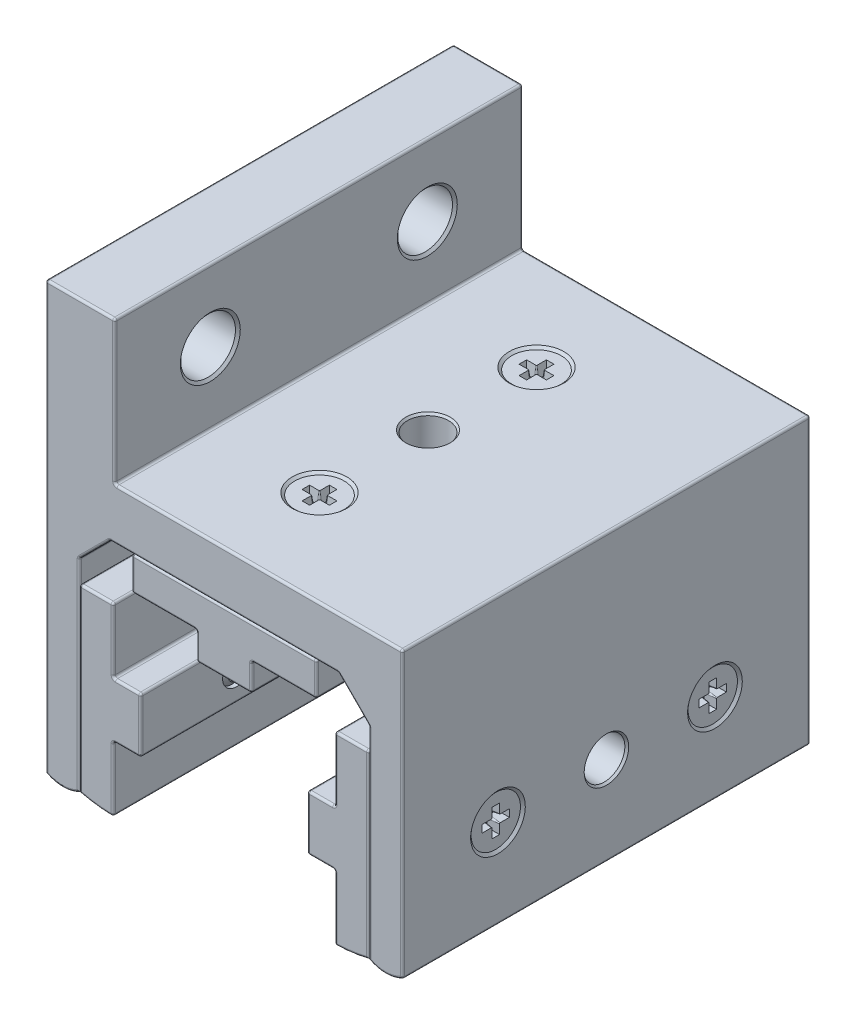
SolidWorks part; units mm, degrees
ref_plane "Front Plane" through (0, 0, 0) normal (0, 0, 1) x (1, 0, 0)
ref_plane "Top Plane" through (0, 0, 0) normal (0, 1, 0) x (1, 0, 0)
ref_plane "Right Plane" through (0, 0, 0) normal (1, 0, 0) x (0, 0, -1)
sketch "Sketch1" plane through (0, 0, 0) normal (0, 0, 1) x (1, 0, 0)
  line L0 (-20.56, -24.865) -> (-20.56, 24.865)
  line L1 (-20.56, 24.865) -> (-12.58, 24.865)
  line L2 (-12.58, 24.865) -> (-12.58, 8.385)
  line L3 (-12.58, 8.385) -> (20.56, 8.385)
  line L4 (20.56, 8.385) -> (20.56, -24.865)
  line L5 (20.56, -24.865) -> (16.66, -24.865)
  line L6 (16.66, -24.865) -> (16.66, -3.565)
  line L8 (10.65, 2.485) -> (-10.65, 2.485)
  line L10 (-16.66, -3.565) -> (-16.66, -24.865)
  line L11 (-16.66, -24.865) -> (-20.56, -24.865)
  line L12 (-16.66, -24.865) -> (-12.76, -24.865)
  line L13 (-12.76, -24.865) -> (-12.76, -17.39)
  line L14 (-12.76, -17.39) -> (-9.585, -17.39)
  line L15 (-9.585, -17.39) -> (-9.585, -11.04)
  line L16 (-9.585, -11.04) -> (-12.76, -11.04)
  line L17 (-12.76, -11.04) -> (-12.76, -3.565)
  line L18 (-12.76, -3.565) -> (-16.66, -3.565)
  line L19 (0, 0) -> (0, 8.385) construction
  line L20 (-16.66, -3.565) -> (-16.66, -1.0356)
  line L21 (-10.65, -1.415) -> (-3.175, -1.415)
  line L22 (-3.175, -1.415) -> (-3.175, -4.59)
  line L23 (-3.175, -4.59) -> (3.175, -4.59)
  line L24 (10.65, -1.415) -> (3.175, -1.415)
  line L25 (-16.66, -1.0356) -> (-13.1394, 2.485)
  line L26 (3.175, -4.59) -> (3.175, -1.415)
  line L27 (-13.1394, 2.485) -> (-10.65, 2.485)
  line L28 (-10.65, -1.415) -> (-10.65, 2.485)
  line L29 (10.65, -1.415) -> (10.65, 2.485)
  line L30 (-20.56, 8.385) -> (0, 8.385) construction
  line L31 (0, 8.385) -> (20.56, 8.385) construction
  line L32 (-14.8997, 0.7247) -> (-13.1394, 2.485) construction
  line L33 (13.1394, 2.485) -> (10.65, 2.485)
  line L34 (16.66, -3.565) -> (16.66, -1.0356)
  line L35 (16.66, -1.0356) -> (13.1394, 2.485)
  point P0 (0, 0)
  point P3 (-20.56, 0)
  point P16 (-9.585, -14.215)
  point P30 (0, -4.59)
  dimension "Length (B)" = 49.73
  dimension "Length (A)" = 41.12
  dimension "Length (C)" = 33.25
  dimension "D2" = 3.9
  dimension "Top to Centerline" = 39.08
  dimension "D3" = 6.35
  dimension "Inside Width" = 7.8
  dimension "Mounting Hole Depth" = 7.98
  dimension "D" = 9.8
  dimension "D4" = 6.35
  dimension "D5" = 3.175
  dimension "D1" = 45
sketch "Sketch2" plane through (0, 0, 0) normal (-1, 0, 0) x (0, 1, 0)
  line L0 (0, -23.5) -> (0, 23.5) construction
  line L3 (8.405, 0) -> (24.865, 0) construction
  line L4 (16.635, -23.5) -> (16.635, 23.5) construction
  circle A0 centre (16.635, -12.5) radius 3.15
  circle A1 centre (-14.215, -12.5) radius 3.15
  point P4 (0, 0)
  point P10 (16.635, 0)
  point P12 (16.635, 12.5)
  point P15 (24.865, 0)
  point P21 (-14.215, 0)
  dimension "Mounting Hole Diameter" = 6.3
  dimension "Length" = 47
  dimension "Hole to Edge" = 11
  dimension "Hole Spacing" = 25
  dimension "Hole to Top" = 8.23
sketch "Sketch3" plane through (0, 0, 0) normal (0, 0, 1) x (1, 0, 0)
  line L0 (-20.56, -24.865) -> (-20.56, 24.865)
  line L1 (-20.56, 24.865) -> (-12.58, 24.865)
  line L2 (-12.58, 24.865) -> (-12.58, 8.385)
  line L3 (-12.58, 8.385) -> (20.56, 8.385)
  line L4 (20.56, 8.385) -> (20.56, -24.865)
  line L5 (20.56, -24.865) -> (16.66, -24.865)
  line L6 (16.66, -24.865) -> (16.66, -1.0356)
  line L7 (16.66, -1.0356) -> (13.1394, 2.485)
  line L8 (13.1394, 2.485) -> (-13.1394, 2.485)
  line L9 (-13.1394, 2.485) -> (-16.66, -1.0356)
  line L10 (-16.66, -1.0356) -> (-16.66, -24.865)
  line L11 (-16.66, -24.865) -> (-20.56, -24.865)
extrude "Boss-Extrude1" add sketch "Sketch3" along normal up to vertex (23.5 mm away) and the other way up to vertex (23.5 mm away) up to point (0, 16.635, 23.5) other way up to point (0, 16.635, -23.5)
sketch "Sketch4" plane through (0, 0, 0) normal (0, 0, 1) x (1, 0, 0)
  line L0 (-16.66, -3.565) -> (-12.76, -3.565)
  line L1 (-12.76, -3.565) -> (-12.76, -11.04)
  line L2 (-12.76, -11.04) -> (-9.585, -11.04)
  line L3 (-9.585, -11.04) -> (-9.585, -17.39)
  line L4 (-9.585, -17.39) -> (-12.76, -17.39)
  line L5 (-12.76, -17.39) -> (-12.76, -24.865)
  line L6 (-12.76, -24.865) -> (-16.66, -24.865)
  line L7 (-16.66, -24.865) -> (-16.66, -3.565)
  line L8 (-10.65, 2.485) -> (-10.65, -1.415)
  line L9 (-10.65, -1.415) -> (-3.175, -1.415)
  line L10 (-3.175, -1.415) -> (-3.175, -4.59)
  line L11 (-3.175, -4.59) -> (3.175, -4.59)
  line L12 (3.175, -4.59) -> (3.175, -1.415)
  line L13 (3.175, -1.415) -> (10.65, -1.415)
  line L14 (10.65, -1.415) -> (10.65, 2.485)
  line L15 (10.65, 2.485) -> (-10.65, 2.485)
  line L16 (0, -11.065) -> (0, -17.365) construction
  line L17 (0, -11.065) -> (0, -17.365) construction
  line L18 (16.66, -24.865) -> (16.66, -3.565)
  line L19 (12.76, -24.865) -> (16.66, -24.865)
  line L20 (12.76, -17.39) -> (12.76, -24.865)
  line L21 (9.585, -17.39) -> (12.76, -17.39)
  line L22 (9.585, -11.04) -> (9.585, -17.39)
  line L23 (12.76, -11.04) -> (9.585, -11.04)
  line L24 (12.76, -3.565) -> (12.76, -11.04)
  line L25 (16.66, -3.565) -> (12.76, -3.565)
extrude "Boss-Extrude2" add sketch "Sketch4" along normal up to vertex (23.5 mm away) and the other way up to vertex (23.5 mm away) separate body up to point (0, 0, 23.5) other way up to point (0, 0, -23.5)
sketch "Sketch5" plane through (0, 0, 0) normal (1, 0, 0) x (0, 0, -1)
  circle A0 centre (-12.5, -14.215) radius 3.15 construction
  circle A1 centre (-12.5, 16.635) radius 3.15 construction
  circle A2 centre (-12.5, -14.215) radius 3.15 construction
  circle A3 centre (-12.5, 16.635) radius 3.15
extrude "Cut-Extrude1" cut sketch "Sketch5" against normal through all both and the other way through all
sketch "Sketch6" plane through (0, 0, 0) normal (1, 0, 0) x (0, 0, -1)
  circle A0 centre (-12.5, -14.215) radius 1.575
  dimension "D1" = 3.15
extrude "Cut-Extrude2" cut sketch "Sketch6" against normal through all both and the other way through all
sketch "Sketch7" plane through (0, 8.385, 0) normal (0, 1, 0) x (1, 0, 0)
  line L1 (0, -9.35) -> (0, -15.65) construction
  line L2 (0, -23.5) -> (0, 23.5) construction
  line L3 (3.15, -12.5) -> (-3.15, -12.5) construction
  line L4 (0, -9.35) -> (0, -15.65) construction
  circle A0 centre (0, -12.5) radius 3.15
extrude "Cut-Extrude3" cut sketch "Sketch7" against normal through all draft 50
sketch "Sketch9" plane through (20.56, 0, 0) normal (1, 0, 0) x (0, 0, -1)
  circle A0 centre (-12.5, -14.215) radius 3.15 construction
  circle A1 centre (-12.5, -14.215) radius 3.15
extrude "Cut-Extrude4" cut sketch "Sketch9" against normal blind 2.54 draft 50
sketch "Sketch10" plane through (-20.56, 0, 0) normal (-1, 0, 0) x (0, 0, 1)
  circle A0 centre (12.5, -14.215) radius 3.15 construction
  circle A1 centre (12.5, -14.215) radius 3.15
extrude "Cut-Extrude5" cut sketch "Sketch10" against normal blind 2.54 draft 50
chamfer "Chamfer2" distance 0.254 angle 50 1 edges at (-12.58, 13.485, 12.5)
sketch "Sketch11" plane through (0, 8.385, 0) normal (0, 1, 0) x (1, 0, 0)
  line L0 (0, -9.35) -> (0, -15.65) construction
  circle A0 centre (0, -12.5) radius 1.575
  dimension "D1" = 3.15
extrude "Cut-Extrude6" cut sketch "Sketch11" against normal through all
sketch "Sketch12" plane through (0, 0, 0) normal (1, 0, 0) x (0, 0, -1)
  line L0 (-12.5, -12.64) -> (-12.5, -11.065) construction
  line L1 (-12.5, -11.8525) -> (0, -11.8525) construction
  circle A0 centre (0, -14.215) radius 2.3625
  circle A1 centre (-12.5, -14.215) radius 1.575 construction
  circle A2 centre (-12.5, -14.215) radius 3.15 construction
extrude "Cut-Extrude7" cut sketch "Sketch12" against normal through all both and the other way through all
sketch "Sketch13" plane through (0, 8.385, 0) normal (0, 1, 0) x (1, 0, 0)
  line L0 (0, -23.5) -> (0, 23.5) construction
  line L1 (-1.575, -12.5) -> (-3.15, -12.5) construction
  line L2 (-2.3625, -12.5) -> (-2.3625, 0) construction
  circle A0 centre (0, 0) radius 2.3625
  circle A1 centre (0, -12.5) radius 1.575 construction
  circle A2 centre (0, -12.5) radius 3.15 construction
extrude "Cut-Extrude8" cut sketch "Sketch13" against normal through all
sketch "Sketch14" plane through (0, 0, 0) normal (0, 0, 1) x (1, 0, 0)
  line L0 (-20.56, -24.865) -> (-20.56, 24.865) construction
  line L1 (-16.66, -3.565) -> (-16.66, -24.865) construction
  line L2 (-16.66, -24.865) -> (-20.56, -24.865) construction
  line L3 (-20.56, -24.357) -> (-20.56, -24.865)
  line L4 (-20.56, -24.865) -> (-20.56, -25.373)
  line L5 (-20.56, -25.373) -> (-16.66, -25.373)
  line L6 (-16.66, -25.373) -> (-16.66, -24.357) construction
  line L7 (-16.66, -24.865) -> (-12.76, -24.865) construction
  line L8 (-16.66, -25.373) -> (-12.76, -25.373)
  line L9 (-12.76, -25.373) -> (-12.76, -24.865)
  line L10 (0, -11.065) -> (0, -17.365) construction
  line L11 (0, -11.065) -> (0, -17.365) construction
  line L12 (16.66, -25.373) -> (16.66, -24.357) construction
  line L13 (12.76, -25.373) -> (12.76, -24.865)
  line L14 (16.66, -25.373) -> (12.76, -25.373)
  line L15 (20.56, -25.373) -> (16.66, -25.373)
  line L16 (20.56, -24.865) -> (20.56, -25.373)
  line L17 (20.56, -24.357) -> (20.56, -24.865)
  arc A0 (-20.56, -24.357) -> (-16.66, -24.357) centre (-18.61, -20.8684) ccw
  arc A1 (-12.76, -24.865) -> (-16.66, -24.357) centre (-12.76, -9.6405) cw
  arc A2 (12.76, -24.865) -> (16.66, -24.357) centre (12.76, -9.6405) ccw
  arc A3 (20.56, -24.357) -> (16.66, -24.357) centre (18.61, -20.8684) cw
  dimension "D1" = 0.508
extrude "Cut-Extrude9" cut sketch "Sketch14" against normal through all both and the other way through all
fillet "Fillet1" radius 0.254 34 edges at (-20.56, 24.865, 0) (-20.56, -24.357, 0) (-16.66, -12.6963, -23.5) (-14.8997, 0.7247, -23.5) (0, 2.485, -23.5) (14.8997, 0.7247, -23.5) (16.66, -12.6963, -23.5) (18.61, -24.865, -23.5) (20.56, -7.986, -23.5) (3.99, 8.385, -23.5) (-12.58, 16.625, -23.5) (-16.57, 24.865, -23.5) (-20.56, 0.254, -23.5) (-18.61, -24.865, -23.5) (-16.57, 24.865, 23.5) (-12.58, 16.625, 23.5) (3.99, 8.385, 23.5) (20.56, -7.986, 23.5) (18.61, -24.865, 23.5) (16.66, -12.6963, 23.5) (14.8997, 0.7247, 23.5) (0, 2.485, 23.5) (-14.8997, 0.7247, 23.5) (-16.66, -12.6963, 23.5) (-18.61, -24.865, 23.5) (-20.56, 0.254, 23.5) (-12.58, 24.865, 0) (20.56, -24.357, 0) (-12.58, 8.385, 0) (20.56, 8.385, 0) (-13.1394, 2.485, 0) (-16.66, -1.0356, 0) (16.66, -1.0356, 0) (13.1394, 2.485, 0)
fillet "Fillet2" radius 0.254 23 edges at (-12.76, -3.565, 0) (-12.76, -11.04, 0) (-12.76, -17.39, 0) (-12.76, -24.865, 0) (-12.76, -21.1275, -23.5) (-11.1725, -17.39, -23.5) (-9.585, -14.215, -23.5) (-11.1725, -11.04, -23.5) (-12.76, -7.3025, -23.5) (-14.71, -3.565, -23.5) (-16.66, -13.961, -23.5) (-14.7265, -24.7375, -23.5) (-14.71, -3.565, 23.5) (-12.76, -7.3025, 23.5) (-11.1725, -11.04, 23.5) (-9.585, -14.215, 23.5) (-11.1725, -17.39, 23.5) (-12.76, -21.1275, 23.5) (-14.7265, -24.7375, 23.5) (-16.66, -13.961, 23.5) (-9.585, -17.39, 0) (-9.585, -11.04, 0) (-16.66, -3.565, 0)
fillet "Fillet3" radius 0.254 23 edges at (12.76, -11.04, 0) (12.76, -3.565, 0) (14.71, -3.565, -23.5) (12.76, -7.3025, -23.5) (11.1725, -11.04, -23.5) (9.585, -14.215, -23.5) (11.1725, -17.39, -23.5) (14.7265, -24.7375, -23.5) (16.66, -13.961, -23.5) (11.1725, -17.39, 23.5) (9.585, -14.215, 23.5) (11.1725, -11.04, 23.5) (12.76, -7.3025, 23.5) (14.71, -3.565, 23.5) (16.66, -13.961, 23.5) (14.7265, -24.7375, 23.5) (12.76, -21.1275, 23.5) (12.76, -24.865, 0) (12.76, -21.1275, -23.5) (12.76, -17.39, 0) (9.585, -11.04, 0) (9.585, -17.39, 0) (16.66, -3.565, 0)
sketch "Sketch15" plane through (20.56, 0, 0) normal (1, 0, 0) x (0, 0, -1)
  circle A2 centre (-12.5, -14.215) radius 2.8452
  circle A3 centre (-12.5, -14.215) radius 2.8452
  dimension "D1" = 0.3048
extrude "Boss-Extrude3" add sketch "Sketch15" against normal blind 2.54 draft 50 from offset 0.254 separate body offset against normal yes
sketch "Sketch16" plane through (20.306, 0, 0) normal (1, 0, 0) x (0, 0, -1)
  circle A0 centre (-12.5, -14.215) radius 1.575 construction
  circle A1 centre (-12.5, -14.215) radius 1.575
extrude "Boss-Extrude4" add sketch "Sketch16" against normal up to surface (10.721 mm away) up to face at (9.585, -14.215, 0)
chamfer "Chamfer3" distance 0.508 angle 50 1 edges at (9.585, -14.215, 10.925)
sketch "Sketch17" plane through (20.306, 0, 0) normal (1, 0, 0) x (0, 0, -1)
  line L1 (-12.754, -15.612) -> (-12.246, -15.612)
  line L2 (-12.754, -15.612) -> (-12.754, -12.818)
  line L3 (-12.754, -12.818) -> (-12.246, -12.818)
  line L4 (-12.246, -15.612) -> (-12.246, -12.818)
  line L5 (-12.5, -12.818) -> (-12.5, -15.612) construction
  line L6 (-12.754, -14.215) -> (-12.246, -14.215) construction
  line L7 (-13.897, -14.469) -> (-11.103, -14.469)
  line L8 (-13.897, -14.469) -> (-13.897, -13.961)
  line L9 (-13.897, -13.961) -> (-11.103, -13.961)
  line L10 (-11.103, -14.469) -> (-11.103, -13.961)
  line L11 (-12.5, -13.961) -> (-12.5, -14.469) construction
  line L12 (-13.897, -14.215) -> (-11.103, -14.215) construction
  point P0 (-12.5, -14.215)
  point P4 (-12.5, -14.215)
  dimension "D1" = 0.508
  dimension "D2" = 0.508
  dimension "D3" = 2.794
extrude "Cut-Extrude10" cut sketch "Sketch17" against normal blind 1.27 contours L9 L8 L7 L2 | L9 L2 L7 L4 | L7 L10 L9 L4 | L2 L9 L4 L3 | L7 L2 L1 L4
fillet "Fillet4" radius 0.254 4 edges at (19.671, -14.469, 12.246) (19.671, -14.469, 12.754) (19.671, -13.961, 12.246) (19.671, -13.961, 12.754)
draft "Draft1" type of draft neutral plane draft angle 8 faces to draft 16 face at (19.671, -13.2625, 12.754) face at (19.671, -13.8603, 12.8547) face at (19.671, -13.961, 13.4525) face at (19.671, -13.961, 11.5475) face at (19.671, -13.8603, 12.1453) face at (19.671, -13.2625, 12.246) face at (19.671, -15.1675, 12.246) face at (19.671, -14.5697, 12.1453) face at (19.671, -14.469, 11.5475) face at (19.671, -14.469, 13.4525) face at (19.671, -14.5697, 12.8547) face at (19.671, -15.1675, 12.754) face at (19.671, -15.612, 12.5) face at (19.671, -14.215, 13.897) face at (19.671, -12.818, 12.5) face at (19.671, -14.215, 11.103) neutral plane through (19.036, 0, 0) neutral plane normal (1, 0, 0) parameters "D1"=8
sketch "Sketch18" plane through (0, 0, 0) normal (1, 0, 0) x (0, 0, -1)
  line L0 (-9.35, 8.385) -> (-15.65, 8.385) construction
  line L1 (-9.35, 8.385) -> (-15.65, 8.385) construction
  line L2 (-15.65, 8.385) -> (-12.5, 5.7418) construction
  line L3 (-12.5, 5.7418) -> (-9.35, 8.385) construction
  line L4 (-12.5, 5.7418) -> (-12.5, 8.131)
  line L5 (23.246, 8.131) -> (-23.246, 8.131) construction
  line L6 (-12.5, 8.131) -> (-15.3473, 8.131)
  line L7 (-15.3473, 8.131) -> (-14.075, 7.0634)
  line L8 (-14.075, 7.0634) -> (-14.075, -4.082)
  line L9 (-13.567, -4.59) -> (-12.5, -4.59)
  line L10 (-12.5, -4.59) -> (-12.5, 5.7418)
  line L11 (-14.075, -4.59) -> (-10.925, -4.59) construction
  line L12 (-14.075, -4.59) -> (-10.925, -4.59) construction
  line L13 (-14.075, -4.082) -> (-13.567, -4.59)
  point P9 (-14.075, -4.59)
  dimension "D1" = 100
revolve "Revolve1" add sketch "Sketch18" angle 360 about L10
sketch "Sketch19" plane through (0, 8.131, 0) normal (0, 1, 0) x (1, 0, 0)
  line L0 (0, -9.35) -> (0, -15.65) construction
  line L1 (-0.254, -13.897) -> (0.254, -13.897)
  line L2 (-0.254, -13.897) -> (-0.254, -11.103)
  line L3 (-0.254, -11.103) -> (0.254, -11.103)
  line L4 (0.254, -13.897) -> (0.254, -11.103)
  line L5 (0, -11.103) -> (0, -13.897) construction
  line L6 (-0.254, -12.5) -> (0.254, -12.5) construction
  line L8 (-1.397, -12.754) -> (1.397, -12.754)
  line L9 (-1.397, -12.754) -> (-1.397, -12.246)
  line L10 (-1.397, -12.246) -> (1.397, -12.246)
  line L11 (1.397, -12.754) -> (1.397, -12.246)
  line L12 (0, -12.246) -> (0, -12.754) construction
  line L13 (-1.397, -12.5) -> (1.397, -12.5) construction
  point P0 (0, -12.5)
  point P6 (0, -12.5)
  dimension "D1" = 2.794
  dimension "D2" = 0.508
extrude "Cut-Extrude11" cut sketch "Sketch19" against normal blind 1.27 contours L8 L2 L1 L4 | L8 L11 L10 L4 | L2 L10 L4 L3 | L10 L9 L8 L2 | L10 L2 L8 L4
fillet "Fillet5" radius 0.254 4 edges at (0.254, 7.496, 12.754) (-0.254, 7.496, 12.754) (0.254, 7.496, 12.246) (-0.254, 7.496, 12.246)
draft "Draft2" type of draft neutral plane draft angle 8 faces to draft 16 parameters "D1"=8
mirror "Mirror1" about plane through (0, 0, 0) normal (1, 0, 0)
pattern_linear "LPattern1" count 2 spacing 25 along (0, 0, -1) of "Cut-Extrude1", "Cut-Extrude2", "Cut-Extrude4", "Cut-Extrude5", "Chamfer2", "Cut-Extrude3", "Cut-Extrude6"
pattern_linear "LPattern2" count 2 spacing 25 along (0, 0, -1)
fillet "Fillet6" radius 0.254 24 edges at (-10.65, 0.535, -23.5) (-3.175, -3.0025, -23.5) (0, -4.59, -23.5) (3.175, -3.0025, -23.5) (10.65, 0.535, -23.5) (0, 2.485, -23.5) (10.65, 0.535, 23.5) (3.175, -3.0025, 23.5) (0, -4.59, 23.5) (-3.175, -3.0025, 23.5) (-10.65, 0.535, 23.5) (0, 2.485, 23.5) (-6.9125, -1.415, 23.5) (-3.175, -1.415, 0) (-6.9125, -1.415, -23.5) (-10.65, -1.415, 0) (6.9125, -1.415, 23.5) (10.65, -1.415, 0) (6.9125, -1.415, -23.5) (3.175, -1.415, 0) (-3.175, -4.59, 0) (3.175, -4.59, 0) (10.65, 2.485, 0) (-10.65, 2.485, 0)
chamfer "Chamfer4" distance 0.2032 angle 50 3 edges at (-2.3625, 8.385, 0) (20.56, -14.215, -2.3625) (-20.56, -14.215, -2.3625)
equation "\"D2@Sketch1\" = \"Inside Width@Sketch1\" / 2"
equation "\"D4@Sketch1\"=\"D3@Sketch1\""
equation "\"D3@LPattern1\"=\"Hole Spacing@Sketch2\""
equation "\"D1@Sketch6\" = \"Mounting Hole Diameter@Sketch2\" / 2"
equation "\"D1@Sketch11\"=\"D1@Sketch6\""
equation "\"D3@LPattern2\"=\"D3@LPattern1\""
equation "\"D1@LPattern2\"=\"D1@LPattern1\""
